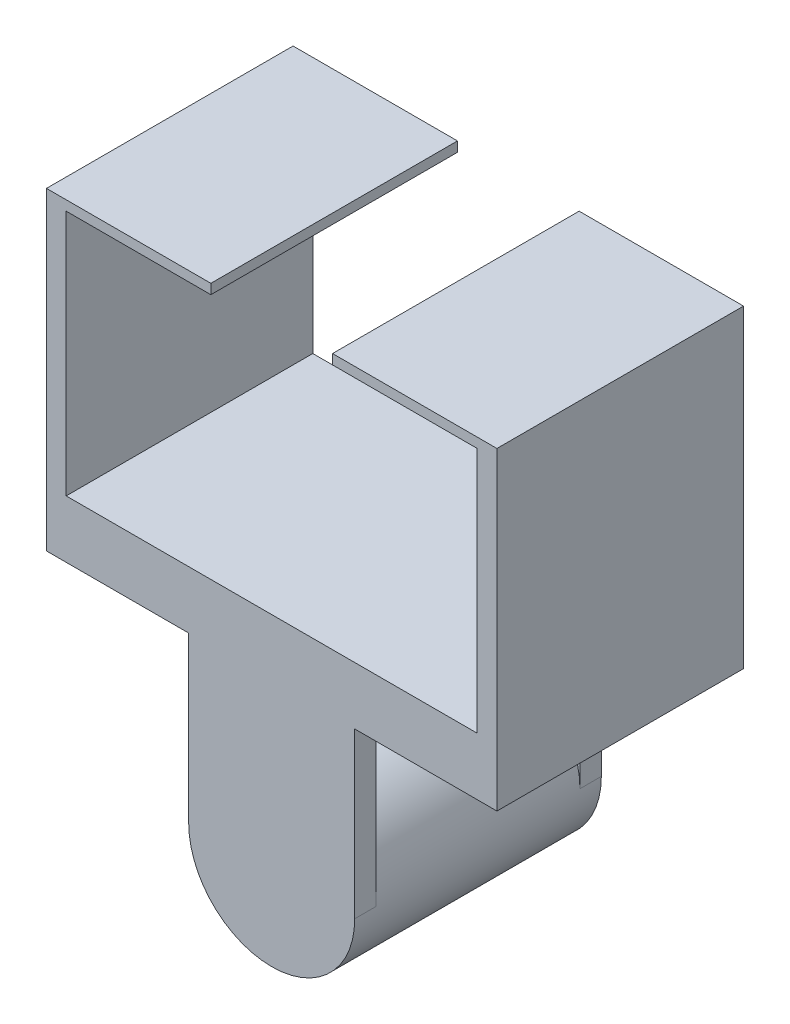
SolidWorks part; units mm, degrees
material "ASTM A36 Steel"
ref_plane "Front Plane" through (0, 0, 0) normal (0, 0, 1) x (1, 0, 0)
ref_plane "Top Plane" through (0, 0, 0) normal (0, 1, 0) x (1, 0, 0)
ref_plane "Right Plane" through (0, 0, 0) normal (1, 0, 0) x (0, 0, -1)
sketch "Sketch1" plane through (0, 0, 0) normal (0, 0, 1) x (1, 0, 0)
  line L0 (0, -55) -> (0, 55) construction
  circle A0 centre (0, -30.1018) radius 12.827
  dimension "D1" = 25.654
extrude "Boss-Extrude1" add sketch "Sketch1" along normal blind 38.1
sketch "Sketch2" plane through (0, 0, 0) normal (0, 0, 1) x (1, 0, 0)
  line L1 (-12.827, -30.1018) -> (12.827, -30.1018)
  line L2 (-12.827, -30.1018) -> (-12.827, -4.7018)
  line L3 (-12.827, -4.7018) -> (12.827, -4.7018)
  line L4 (12.827, -30.1018) -> (12.827, -4.7018)
  circle A0 centre (0, -30.1018) radius 12.827 construction
  dimension "D1" = 25.4
  dimension "DA" = 25.654
extrude "Boss-Extrude2" add sketch "Sketch2" along normal blind 3.302
sketch "Sketch8" plane through (0, -4.7018, 0) normal (0, 1, 0) x (1, 0, 0)
  line L0 (0, -14.1097) -> (0, 14.1097) construction
  line L1 (-31.75, 0) -> (31.75, 0)
  line L2 (-31.75, 0) -> (-31.75, -38.1)
  line L3 (-31.75, -38.1) -> (31.75, -38.1)
  line L4 (31.75, 0) -> (31.75, -38.1)
  dimension "D1" = 63.5
  dimension "D2" = 31.75
  dimension "D3" = 38.1
extrude "Boss-Extrude6" add sketch "Sketch8" along normal blind 8.89
sketch "Sketch10" plane through (31.75, 0, 0) normal (1, 0, 0) x (0, 0, -1)
  line L1 (-38.1, -4.7018) -> (0, -4.7018)
  line L2 (-38.1, -4.7018) -> (-38.1, 42.2882)
  line L3 (-38.1, 42.2882) -> (0, 42.2882)
  line L4 (0, -4.7018) -> (0, 42.2882)
  dimension "D1" = 46.99
extrude "Boss-Extrude7" add sketch "Sketch10" along normal blind 3.048
sketch "Sketch11" plane through (-31.75, 0, 0) normal (-1, 0, 0) x (0, 0, 1)
  line L0 (0, -25.9143) -> (0, 25.9143) construction
  line L1 (38.1, -4.7018) -> (0, -4.7018)
  line L2 (38.1, -4.7018) -> (38.1, 42.2882)
  line L3 (38.1, 42.2882) -> (0, 42.2882)
  line L4 (0, -4.7018) -> (0, 42.2882)
  dimension "D1" = 46.99
extrude "Boss-Extrude8" add sketch "Sketch11" along normal blind 3.048
sketch "Sketch13" plane through (0, 42.2882, 0) normal (0, 1, 0) x (1, 0, 0)
  line L0 (-36.6014, 0) -> (36.6014, 0) construction
  line L1 (34.798, -38.1) -> (9.398, -38.1)
  line L2 (34.798, -38.1) -> (34.798, 0)
  line L3 (34.798, 0) -> (9.398, 0)
  line L4 (9.398, -38.1) -> (9.398, 0)
  dimension "D1" = 25.4
extrude "Boss-Extrude9" add sketch "Sketch13" along normal blind 1.524
sketch "Sketch14" plane through (0, 42.2882, 0) normal (0, 1, 0) x (1, 0, 0)
  line L1 (-34.798, -38.1) -> (-9.398, -38.1)
  line L2 (-34.798, -38.1) -> (-34.798, 0)
  line L3 (-34.798, 0) -> (-9.398, 0)
  line L4 (-9.398, -38.1) -> (-9.398, 0)
  dimension "D1" = 25.4
extrude "Boss-Extrude10" add sketch "Sketch14" along normal blind 1.524
sketch "Sketch16" plane through (0, 0, 38.1) normal (0, 0, 1) x (1, 0, 0)
  line L0 (-12.827, -30.1018) -> (-12.827, -4.7018)
  line L1 (-12.827, -4.7018) -> (12.827, -4.7018)
  line L2 (12.827, -4.7018) -> (12.827, -30.1018)
  line L3 (12.827, -30.1018) -> (-12.827, -30.1018)
extrude "Boss-Extrude12" add sketch "Sketch16" against normal blind 3.302
equation "\"F\"= 600"
equation "\"Sy\"= 36000"
equation "\"SF\"= 4"
equation "\"def\"= 0.005in"
equation "\"W\"= \"F\" * 2"
equation "\"LA\"= 1.5in"
equation "\"LB\"= \"LA\" / 3"
equation "\"a\"= 0.498in"
equation "\"b\"= 0.9992in"
equation "\"c\"= 1.499in"
equation "\"WC\"= \"a\" + 2 * \"b\""
equation "\"M_A\"= \"W\" * ( \"LA\" / 2 )"
equation "\"Z_A\"= \"M_A\" * ( \"SF\" / \"Sy\" )"
equation "\"D_A\"= 2 * ( 4 * \"Z_A\" / pi ) ^ ( 1 / 3 )"
equation "\"WB\"= \"D_A\""
equation "\"AB\"= \"W\" * \"SF\" / \"Sy\""
equation "\"HB\"= \"AB\" / \"WB\""
equation "\"MC\"= \"W\" * \"LA\" / 4"
equation "\"Z_C\"= \"MC\" * \"SF\" / \"Sy\""
equation "\"HC\"= ( 6 * \"Z_C\" / \"WC\" ) ^ ( 1 / 2 )"
equation "\"HD\"= \"c\""
equation "\"AD\"= \"F\" * \"SF\" / \"Sy\""
equation "\"WD\"= \"AD\" / \"HD\""
equation "\"WE\"= \"b\" + \"WD\""
equation "\"AE\"= \"F\" * \"SF\" / \"Sy\""
equation "\"HE\"= \"AE\" / \"WE\""
